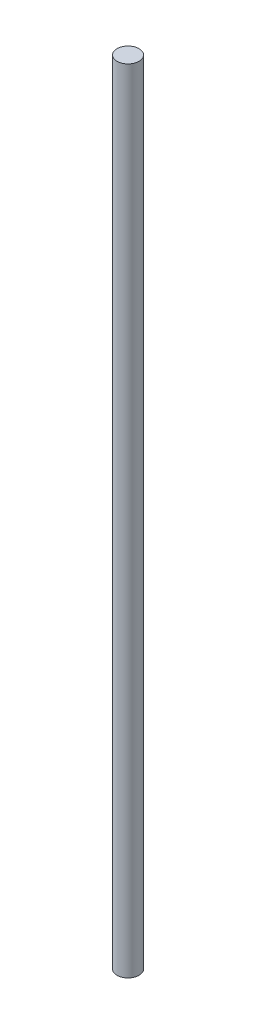
SolidWorks part; units mm, degrees
ref_plane "정면" through (0, 0, 0) normal (0, 0, 1) x (1, 0, 0)
ref_plane "윗면" through (0, 0, 0) normal (0, 1, 0) x (1, 0, 0)
ref_plane "우측면" through (0, 0, 0) normal (1, 0, 0) x (0, 0, -1)
sketch "스케치1" plane through (0, 0, 0) normal (0, 1, 0) x (1, 0, 0)
  circle A0 centre (0, 0) radius 5
  dimension "D1" = 10
extrude "보스-돌출1" add sketch "스케치1" along normal blind 360
